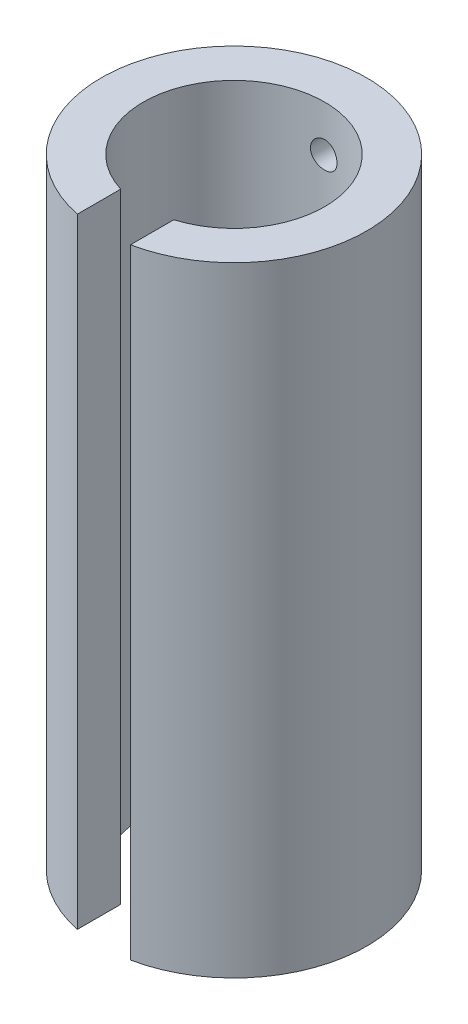
SolidWorks part; units mm, degrees
ref_plane "정면" through (0, 0, 0) normal (0, 0, 1) x (1, 0, 0)
ref_plane "윗면" through (0, 0, 0) normal (0, 1, 0) x (1, 0, 0)
ref_plane "우측면" through (0, 0, 0) normal (1, 0, 0) x (0, 0, -1)
sketch "스케치1" plane through (0, 0, 0) normal (0, 1, 0) x (1, 0, 0)
  circle A0 centre (0, 0) radius 15
  circle A1 centre (0, 0) radius 10.25
extrude "보스-돌출1" add sketch "스케치1" along normal blind 150
sketch3d "3D스케치1"
  point P0 (-0.2132, 108.9998, -14.9985)
ref_plane "평면1" through (0, 0, -14.9985) normal (0, 0, -1) x (-1, 0, 0)
sketch "스케치2" plane through (0, 0, -14.9985) normal (0, 0, -1) x (-1, 0, 0)
  line L0 (0, 150) -> (0, 136.8391)
  line L1 (15, 150) -> (-15, 150) construction
  line L2 (0, 136.8391) -> (0, 122.3311)
  line L3 (0, 122.3311) -> (0, 106.7615)
  line L4 (0, 106.7615) -> (0, 91.8997)
  line L5 (0, 91.8997) -> (0, 76.507)
  line L6 (0, 76.507) -> (0, 64.8299)
  line L7 (0, 64.8299) -> (0, 48.9064)
  line L8 (0, 48.9064) -> (0, 36.2079)
  line L9 (0, 36.2079) -> (0, 21.2079)
  line L10 (0, 21.2079) -> (0, 11.8058)
  circle A0 centre (0, 11.8058) radius 1.5
  circle A1 centre (0, 21.2079) radius 1.5
  circle A2 centre (0, 36.2079) radius 1.5
  circle A3 centre (0, 48.9064) radius 1.5
  circle A4 centre (0, 56.8681) radius 1.5
  circle A5 centre (0, 64.8299) radius 1.5
  circle A6 centre (0, 77.0544) radius 1.5
  circle A7 centre (0, 91.8997) radius 1.5
  circle A8 centre (0, 106.7615) radius 1.5
  circle A9 centre (0, 122.3311) radius 1.5
  circle A10 centre (0, 136.8391) radius 1.5
extrude "컷-돌출1" cut sketch "스케치2" against normal through all both and the other way through all contours A10 | A9 | A8 | A7 | A6 | A5 | A4 | A3 | A2 | A1 | A0
sketch "스케치3" plane through (0, 150, 0) normal (0, 1, 0) x (1, 0, 0)
  circle A0 centre (0, 0) radius 22.1427
extrude "컷-돌출2" cut sketch "스케치3" against normal blind 80
sketch "스케치4" plane through (0, 0, 0) normal (0, -1, 0) x (1, 0, 0)
  line L2 (0, 10.25) -> (0, 15.0983)
  line L3 (0, 15.0983) -> (-3, 15.0983)
  line L4 (-3, 10.25) -> (-3, 15.0983)
  line L7 (0, 15.0983) -> (3, 15.0983)
  line L8 (3, 10.25) -> (3, 15.0983)
  line L9 (-3, 10.25) -> (3, 10.25)
  line L10 (-3, 10.25) -> (-3, 9.1174)
  line L11 (-3, 9.1174) -> (3, 9.1174)
  line L12 (3, 10.25) -> (3, 9.1174)
  line L13 (-3, 9.1174) -> (3, 9.1174)
  line L14 (-3, 9.1174) -> (-3, 15.0983)
  line L15 (-3, 15.0983) -> (3, 15.0983)
  line L16 (3, 9.1174) -> (3, 15.0983)
  circle A0 centre (0, 0) radius 10.25 construction
  dimension "D1" = 3
  dimension "D2" = 3
sketch "스케치5" plane through (0, 0, 0) normal (0, -1, 0) x (1, 0, 0)
  line L1 (-3, 9.1174) -> (3, 9.1174)
  line L2 (-3, 9.1174) -> (-3, 15.0983)
  line L3 (-3, 15.0983) -> (3, 15.0983)
  line L4 (3, 9.1174) -> (3, 15.0983)
extrude "컷-돌출3" cut sketch "스케치5" against normal blind 80
